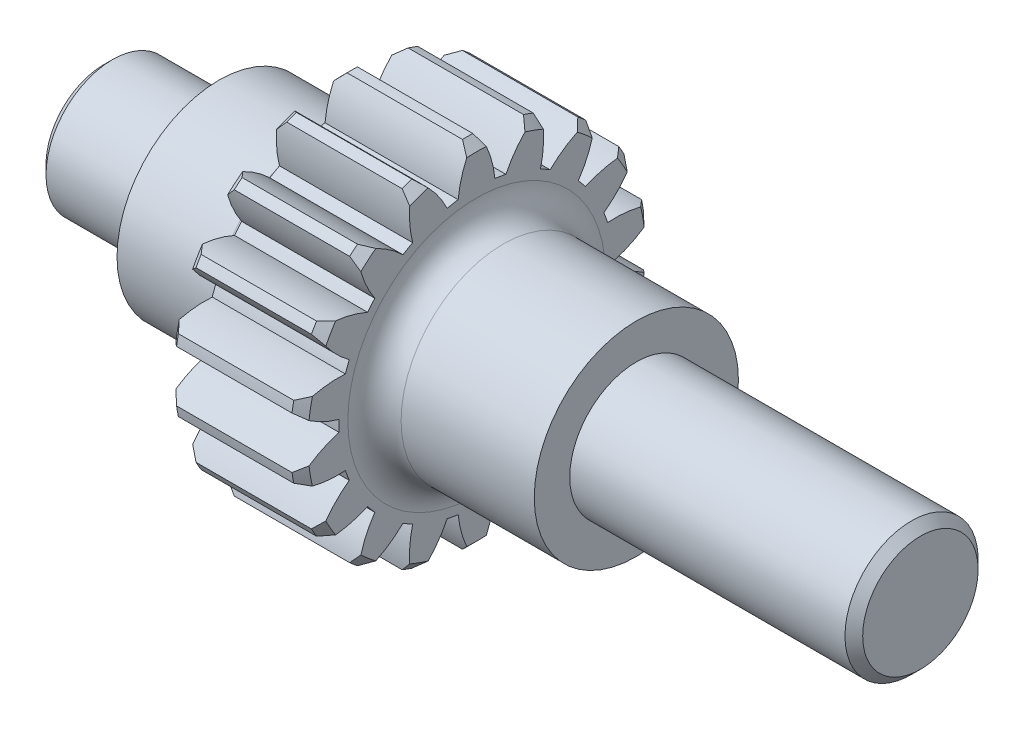
SolidWorks part; units mm, degrees
material "Alloy Steel"
ref_plane "Front Plane" through (0, 0, 0) normal (0, 0, 1) x (1, 0, 0)
ref_plane "Top Plane" through (0, 0, 0) normal (0, 1, 0) x (1, 0, 0)
ref_plane "Right Plane" through (0, 0, 0) normal (1, 0, 0) x (0, 0, -1)
sketch "Sketch1" plane through (0, 0, 0) normal (0, 0, 1) x (1, 0, 0)
  line L0 (0, 0) -> (0, 7.5)
  line L1 (0, 7.5) -> (13, 7.5)
  line L2 (13, 7.5) -> (13, 11.5)
  line L3 (13, 11.5) -> (27, 11.5)
  line L4 (27, 11.5) -> (27, 15.5)
  line L5 (27, 15.5) -> (42, 15.5)
  line L6 (42, 15.5) -> (42, 11.5)
  line L7 (42, 11.5) -> (60, 11.5)
  line L8 (60, 11.5) -> (60, 7.5)
  line L9 (60, 7.5) -> (92, 7.5)
  line L10 (0, 0) -> (69.4619, 0) construction
  line L11 (92, 7.5) -> (92, 0)
  line L12 (0, 0) -> (92, 0)
  point P3 (66.6984, 8.5428)
  dimension "D1" = 15
  dimension "D2" = 23
  dimension "D3" = 13
  dimension "D4" = 14
  dimension "D5" = 15
  dimension "D6" = 31
  dimension "D7" = 18
  dimension "D8" = 15
  dimension "D9" = 32
revolve "Revolve1" add sketch "Sketch1" angle 360 about L10
sketch "Sketch7" plane through (42, 0, 0) normal (1, 0, 0) x (0, 0, -1)
  line L0 (0, 0) -> (0, 22.8546) construction
  circle A0 centre (0, 0) radius 15.5 construction
  arc A1 (2.07, 15.3612) -> (-2.07, 15.3612) centre (0, 0) ccw
  arc A2 (0.58, 19.9916) -> (-0.58, 19.9916) centre (0, 0) ccw
  arc A3 (-0.58, 19.9916) -> (-2.07, 15.3612) centre (9.4917, 14.1957) ccw
  arc A4 (0.58, 19.9916) -> (2.07, 15.3612) centre (-9.4917, 14.1957) cw
  point P10 (0, 0)
  point P14 (-1.57, 17.7552)
  dimension "D1" = 40
  dimension "D2" = 1.16
  dimension "D3" = 2.07
  dimension "D4" = 1.57
extrude "Boss-Extrude1" add sketch "Sketch7" against normal blind 15
chamfer "Chamfer1" distance 1 angle 45 2 edges at (42, 20, 0) (27, 20, 0)
pattern_circular "CirPattern1" count 18 over 360 about axis through (0, 0, 0) along (1, 0, 0) of "Boss-Extrude1", "Chamfer1"
fillet "Fillet1" radius 3 2 edges at (42, 0, 11.5) (27, 0, 11.5)
chamfer "Chamfer2" distance 1 angle 45 2 edges at (0, 0, 7.5) (92, 0, 7.5)
